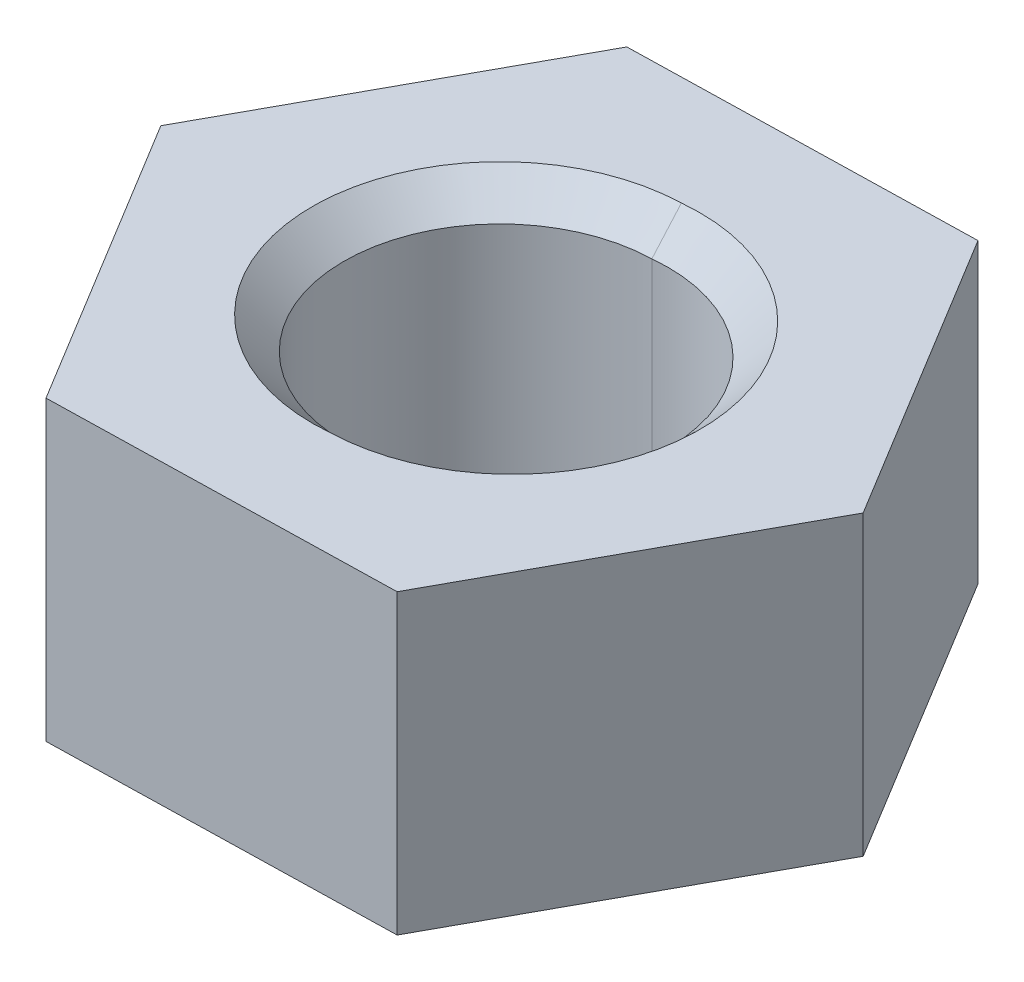
SolidWorks part; units mm, degrees
ref_plane "Front Plane" through (0, 0, 0) normal (0, 0, 1) x (1, 0, 0)
ref_plane "Top Plane" through (0, 0, 0) normal (0, 1, 0) x (1, 0, 0)
ref_plane "Right Plane" through (0, 0, 0) normal (1, 0, 0) x (0, 0, -1)
sketch "Sketch8" plane through (0, 0, 0) normal (0, 1, 0) x (1, 0, 0)
  line L1 (2.4008, -3.9458) -> (4.6176, 0.1063)
  line L2 (4.6176, 0.1063) -> (2.2168, 4.0521)
  line L3 (2.2168, 4.0521) -> (-2.4008, 3.9458)
  line L4 (-2.4008, 3.9458) -> (-4.6176, -0.1063)
  line L5 (-4.6176, -0.1063) -> (-2.2168, -4.0521)
  line L6 (-2.2168, -4.0521) -> (2.4008, -3.9458)
  circle A0 centre (0, 0) radius 4 construction
  dimension "D1" = 8
extrude "Boss-Extrude2" add sketch "Sketch8" along normal blind 4
hole_wizard "M5 Tapped Hole3" positions "3DSketch10" profile "Sketch11" tap size "M5" standard "ISO" end condition through all
sketch3d "3DSketch10"
  point P0 (-0.1323, 4, 0.0288)
  point P3 (-0.1323, 4, 0.0288)
  point P5 (-0.1323, 4, 0.0288)
  point P7 (0.0226, 4, 0.0189)
  point P9 (0.0226, 4, 0.0189)
sketch "Sketch11" plane through (-0.1323, 4, 0.0288) normal (1, 0, 0) x (0, 0, 1)
  line L0 (0, 0) -> (0, 4)
  line L1 (0, 4) -> (2.1, 4)
  line L2 (2.1, 4) -> (2.1, 0.425)
  line L3 (2.1, 0.425) -> (2.525, 0)
  line L5 (2.525, 0) -> (0, 0)
  line L6 (-2.1, 0.425) -> (-2.525, 0) construction
  line L11 (0, -6.35) -> (0, 107.95) construction
  dimension "Thru Tap Drill Dia." = 4.2
  dimension "Thru Tap Drill Depth" = 4
  dimension "Near C'Sink Dia." = 5.05
  dimension "Near C'Sink Angle" = 90
cosmetic thread "Hole Thread6"
cosmetic thread "Hole Thread7"
cosmetic thread "Hole Thread8"
cosmetic thread "Hole Thread9"
cosmetic thread "Hole Thread10"
